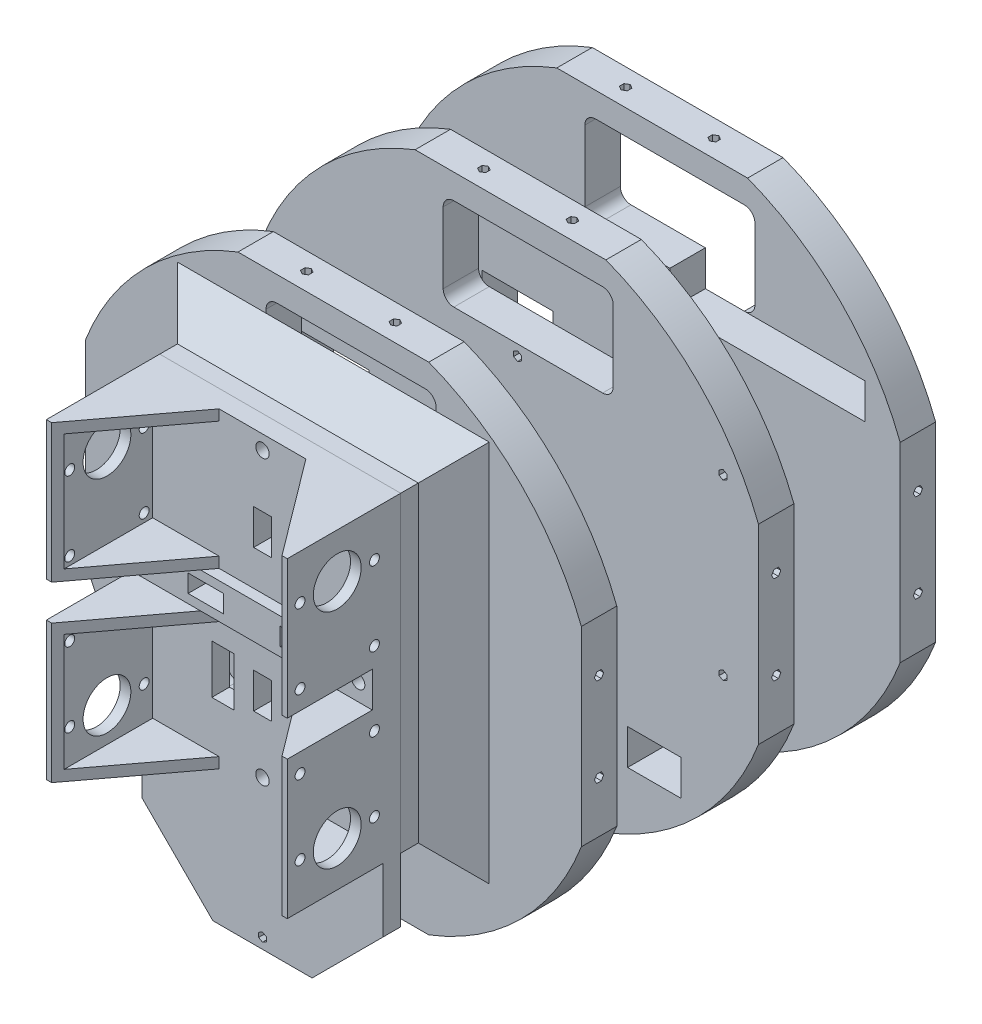
SolidWorks part; units mm, degrees
ref_plane "正面" through (0, 0, 0) normal (0, 0, 1) x (1, 0, 0)
ref_plane "平面" through (0, 0, 0) normal (0, 1, 0) x (1, 0, 0)
ref_plane "右側面" through (0, 0, 0) normal (1, 0, 0) x (0, 0, -1)
sketch "ｽｹｯﾁ5" plane through (0, 0, 0) normal (0, 1, 0) x (1, 0, 0)
  line L0 (-34, -32) -> (-34, 0)
  line L1 (-34, 0) -> (-10, 0)
  line L2 (-10, 0) -> (-34, -32)
  line L3 (-88, 0) -> (88, 0) construction
  dimension "D1" = 24
  dimension "D2" = 32
  dimension "D3" = 10
extrude "ﾎﾞｽ - 押し出し3" add sketch "ｽｹｯﾁ5" against normal blind 39 from offset 5 offset against normal yes
shell "ｼｪﾙ2" thickness 3
sketch "ｽｹｯﾁ7" plane through (-31, 0, 0) normal (1, 0, 0) x (0, 0, -1)
  line L0 (-3, -41) -> (-3, -8) construction
  line L1 (-26.4, -31.4) -> (-5.4, -31.4) construction
  line L2 (-26.4, -31.4) -> (-26.4, -10.4) construction
  line L3 (-26.4, -10.4) -> (-5.4, -10.4) construction
  line L4 (-5.4, -31.4) -> (-5.4, -10.4) construction
  line L5 (-3, -8) -> (-28, -8) construction
  circle A0 centre (-15.9, -31.4) radius 6.75
  circle A1 centre (-26.4, -31.4) radius 1.4
  circle A2 centre (-5.4, -31.4) radius 1.4
  circle A3 centre (-5.4, -10.4) radius 1.4
  circle A4 centre (-26.4, -10.4) radius 1.4
  point P10 (-15.9, -31.4)
  dimension "D3" = 2.8
  dimension "D6" = 13.5
  dimension "D1" = 21
  dimension "D2" = 21
  dimension "D4" = 2.4
  dimension "D5" = 2.4
extrude "ｶｯﾄ - 押し出し5" cut sketch "ｽｹｯﾁ7" against normal through all
sketch "ｽｹｯﾁ1" plane through (0, 0, 0) normal (0, 0, 1) x (1, 0, 0)
  line L0 (-34, -44) -> (-34, -5) construction
  line L1 (34, -44) -> (-34, -44)
  line L2 (34, -44) -> (34, 44)
  line L3 (34, 44) -> (-34, 44)
  line L4 (-34, -44) -> (-34, 44)
  line L5 (34, -44) -> (-34, 44) construction
  line L6 (34, 44) -> (-34, -44) construction
  line L7 (-34, -44) -> (-10, -44) construction
  point P0 (0, 0)
extrude "ﾎﾞｽ - 押し出し1" add sketch "ｽｹｯﾁ1" along normal blind 3 and the other way blind 2 contours L4 L1 L2 L3
sketch "ｽｹｯﾁ8" plane through (0, 0, 0) normal (0, 0, 1) x (1, 0, 0)
  line L0 (-34, -44) -> (-34, -5) construction
  line L1 (-34, -5) -> (-22.8121, -5)
  line L2 (-34, -5) -> (-34, -44)
  line L3 (-34, -44) -> (-22.8121, -44)
  line L4 (-22.8121, -5) -> (-22.8121, -44)
extrude "ｶｯﾄ - 押し出し6" cut sketch "ｽｹｯﾁ8" against normal blind 2 from vertex at 32 starting at point (-34, -5, 32)
mirror "ﾐﾗｰ1" about plane through (0, 0, 0) normal (1, 0, 0) of bodies 136 101
mirror "ﾐﾗｰ2" about plane through (0, 0, 0) normal (0, 1, 0) of bodies 134
sketch "ｽｹｯﾁ9" plane through (0, 0, 3) normal (0, 0, 1) x (1, 0, 0)
  circle A0 centre (-30, 0) radius 1.9
  circle A1 centre (0, 40) radius 1.9
  circle A2 centre (30, 0) radius 1.9
  circle A3 centre (0, -40) radius 1.9
  dimension "D1" = 3.8
  dimension "D2" = 30
  dimension "D3" = 30
  dimension "D4" = 40
  dimension "D5" = 40
extrude "ｶｯﾄ - 押し出し7" cut sketch "ｽｹｯﾁ9" against normal blind 10
sketch "ｽｹｯﾁ10" plane through (0, 0, 3) normal (0, 0, 1) x (1, 0, 0)
  line L1 (2.5, -25) -> (-2.5, -25)
  line L2 (2.5, -25) -> (2.5, -15)
  line L3 (2.5, -15) -> (-2.5, -15)
  line L4 (-2.5, -25) -> (-2.5, -15)
  line L5 (2.5, -25) -> (-2.5, -15) construction
  line L6 (2.5, -15) -> (-2.5, -25) construction
  line L7 (2.5, 15) -> (-2.5, 15)
  line L8 (2.5, 15) -> (2.5, 25)
  line L9 (2.5, 25) -> (-2.5, 25)
  line L10 (-2.5, 15) -> (-2.5, 25)
  line L11 (2.5, 15) -> (-2.5, 25) construction
  line L12 (2.5, 25) -> (-2.5, 15) construction
  point P0 (0, -20)
  point P5 (0, 20)
  dimension "D1" = 5
  dimension "D2" = 10
  dimension "D3" = 20
  dimension "D4" = 20
extrude "ｶｯﾄ - 押し出し8" cut sketch "ｽｹｯﾁ10" against normal blind 10
sketch "ｽｹｯﾁ11" plane through (0, 0, 3) normal (0, 0, 1) x (1, 0, 0)
  line L0 (31, 38.15) -> (31, 24.65) construction
  line L1 (14.3, 13.75) -> (8, 13.75)
  line L2 (14.3, 13.75) -> (14.3, 27.55)
  line L3 (14.3, 27.55) -> (8, 27.55)
  line L4 (8, 13.75) -> (8, 27.55)
  line L5 (14.3, 13.75) -> (8, 27.55) construction
  line L6 (14.3, 27.55) -> (8, 13.75) construction
  line L7 (-8, -27.55) -> (-14.3, -27.55)
  line L8 (-8, -27.55) -> (-8, -13.75)
  line L9 (-8, -13.75) -> (-14.3, -13.75)
  line L10 (-14.3, -27.55) -> (-14.3, -13.75)
  line L11 (-8, -27.55) -> (-14.3, -13.75) construction
  line L12 (-8, -13.75) -> (-14.3, -27.55) construction
  line L13 (31, 38.15) -> (31, 24.65)
  line L15 (-31, -38.15) -> (-31, -24.65) construction
  line L16 (-31, -38.15) -> (-31, -24.65)
  point P0 (11.15, 20.65)
  point P5 (-11.15, -20.65)
  point P15 (31, 31.4)
  point P20 (-31, -31.4)
  dimension "D1" = 6.3
  dimension "D2" = 3.85
  dimension "D3" = 17.65
  dimension "D4" = 23
  dimension "D5" = 3.85
  dimension "D6" = 23
extrude "ｶｯﾄ - 押し出し9" cut sketch "ｽｹｯﾁ11" against normal blind 10 contours L10 L7 L8 L9 | L4 L1 L2 L3
sketch "ｽｹｯﾁ12" plane through (0, 0, 3) normal (0, 0, 1) x (1, 0, 0)
  line L1 (-8, -2.5) -> (-18, -2.5)
  line L2 (-8, -2.5) -> (-8, 2.5)
  line L3 (-8, 2.5) -> (-18, 2.5)
  line L4 (-18, -2.5) -> (-18, 2.5)
  line L5 (-8, -2.5) -> (-18, 2.5) construction
  line L6 (-8, 2.5) -> (-18, -2.5) construction
  line L7 (18, -2.5) -> (8, -2.5)
  line L8 (18, -2.5) -> (18, 2.5)
  line L9 (18, 2.5) -> (8, 2.5)
  line L10 (8, -2.5) -> (8, 2.5)
  line L11 (18, -2.5) -> (8, 2.5) construction
  line L12 (18, 2.5) -> (8, -2.5) construction
  point P0 (-13, 0)
  point P5 (13, 0)
  dimension "D1" = 5
  dimension "D2" = 10
  dimension "D3" = 13
  dimension "D4" = 13
extrude "ｶｯﾄ - 押し出し10" cut sketch "ｽｹｯﾁ12" against normal blind 10
sketch "ｽｹｯﾁ13" plane through (0, -44, 0) normal (0, -1, 0) x (1, 0, 0)
  line L0 (34, -2) -> (34, 30) construction
  line L1 (-34, -2) -> (34, -2)
  line L2 (-34, -2) -> (-34, 3)
  line L3 (-34, 3) -> (34, 3)
  line L4 (34, -2) -> (34, 3)
  line L5 (12.25, 3) -> (-12.25, 3) construction
extrude "ﾎﾞｽ - 押し出し4" add sketch "ｽｹｯﾁ13" along normal blind 38
chamfer "面取り2" distance 20 angle 45 2 edges at (-34, -82, 0.5) (34, -82, 0.5)
sketch "ｽｹｯﾁ14" plane through (0, 0, -2) normal (0, 0, -1) x (-1, 0, 0)
  line L0 (14, -82) -> (-14, -82) construction
  line L1 (23.4, -79) -> (-23.4, -79) construction
  line L2 (23.4, -79) -> (23.4, -47.08) construction
  line L3 (23.4, -47.08) -> (-23.4, -47.08) construction
  line L4 (-23.4, -79) -> (-23.4, -47.08) construction
  line L5 (23.4, -79) -> (-23.4, -47.08) construction
  line L6 (23.4, -47.08) -> (-23.4, -79) construction
  line L8 (-23.4, -45.83) -> (-24.4825, -46.455)
  line L9 (-24.4825, -46.455) -> (-24.4825, -47.705)
  line L10 (-24.4825, -47.705) -> (-23.4, -48.33)
  line L11 (-23.4, -48.33) -> (-22.3175, -47.705)
  line L12 (-22.3175, -47.705) -> (-22.3175, -46.455)
  line L13 (-22.3175, -46.455) -> (-23.4, -45.83)
  line L14 (23.4, -45.83) -> (22.3175, -46.455)
  line L15 (22.3175, -46.455) -> (22.3175, -47.705)
  line L16 (22.3175, -47.705) -> (23.4, -48.33)
  line L17 (23.4, -48.33) -> (24.4825, -47.705)
  line L18 (24.4825, -47.705) -> (24.4825, -46.455)
  line L19 (24.4825, -46.455) -> (23.4, -45.83)
  line L20 (0, -77.75) -> (-1.0825, -78.375)
  line L21 (-1.0825, -78.375) -> (-1.0825, -79.625)
  line L22 (-1.0825, -79.625) -> (0, -80.25)
  line L23 (0, -80.25) -> (1.0825, -79.625)
  line L24 (1.0825, -79.625) -> (1.0825, -78.375)
  line L25 (1.0825, -78.375) -> (0, -77.75)
  circle A0 centre (-23.4, -47.08) radius 1.5
  circle A1 centre (23.4, -47.08) radius 1.5
  circle A2 centre (0, -79) radius 1.5
  circle A3 centre (-23.4, -47.08) radius 1.0825 construction
  circle A4 centre (23.4, -47.08) radius 1.0825 construction
  circle A5 centre (0, -79) radius 1.0825 construction
  point P0 (0, -63.04)
  point P12 (0, -82)
  dimension "D3" = 3
  dimension "D1" = 46.8
  dimension "D2" = 31.92
  dimension "D4" = 3
  dimension "D5" = 2.5
extrude "ｶｯﾄ - 押し出し11" cut sketch "ｽｹｯﾁ14" against normal blind 35 contours L24 L25 L20 L21 L22 L23 | L12 L13 L8 L9 L10 L11 | L18 L19 L14 L15 L16 L17
sketch "ｽｹｯﾁ15" plane through (0, 0, 3) normal (0, 0, 1) x (1, 0, 0)
  line L0 (-18, 2.5) -> (-18, -2.5) construction
  line L1 (34, -5) -> (-34, -5)
  line L2 (34, -5) -> (34, 5)
  line L3 (34, 5) -> (-34, 5)
  line L4 (-34, -5) -> (-34, 5)
  line L5 (-18, -2.5) -> (-8, -2.5) construction
  line L6 (-8, 2.5) -> (-18, 2.5) construction
  line L7 (-8, -2.5) -> (-8, 2.5) construction
  line L8 (8, 2.5) -> (8, -2.5) construction
  line L9 (18, 2.5) -> (8, 2.5) construction
  line L10 (8, -2.5) -> (18, -2.5) construction
  line L11 (18, -2.5) -> (18, 2.5) construction
  line L12 (-18, 2.5) -> (-18, -2.5)
  line L13 (-18, -2.5) -> (-8, -2.5)
  line L14 (-8, 2.5) -> (-18, 2.5)
  line L15 (-8, -2.5) -> (-8, 2.5)
  line L16 (8, 2.5) -> (8, -2.5)
  line L17 (18, 2.5) -> (8, 2.5)
  line L18 (8, -2.5) -> (18, -2.5)
  line L19 (18, -2.5) -> (18, 2.5)
  circle A0 centre (30, 0) radius 1.9 construction
  circle A1 centre (-30, 0) radius 1.9 construction
  circle A2 centre (30, 0) radius 1.9
  circle A3 centre (-30, 0) radius 1.9
extrude "ﾎﾞｽ - 押し出し5" add sketch "ｽｹｯﾁ15" along normal blind 3
sketch "ｽｹｯﾁ16" plane through (0, 0, -2) normal (0, 0, -1) x (-1, 0, 0)
  line L0 (-19, -29) -> (-19, 29) construction
  line L5 (34, -44) -> (-34, -44)
  line L6 (34, -44) -> (34, 44)
  line L7 (34, 44) -> (-34, 44)
  line L8 (-34, -44) -> (-34, 44)
  line L9 (34, -44) -> (-34, 44) construction
  line L10 (34, 44) -> (-34, -44) construction
  line L11 (19, 29) -> (-19, 29) construction
  line L12 (19, -29) -> (19, 29) construction
  line L13 (19, -29) -> (-19, -29) construction
  line L14 (-25, -35) -> (-25, 35)
  line L15 (25, 35) -> (-25, 35)
  line L16 (25, -35) -> (25, 35)
  line L17 (25, -35) -> (-25, -35)
  circle A1 centre (0, -5) radius 80 construction
  point P4 (0, 0)
  dimension "D1" = 160
  dimension "D2" = 5
  dimension "D3" = 15
  dimension "D4" = 6
extrude "ﾎﾞｽ - 押し出し7" add sketch "ｽｹｯﾁ16" along normal blind 10 separate body
sketch "ｽｹｯﾁ48" plane through (0, 0, -12) normal (0, 0, -1) x (-1, 0, 0)
  line L4 (-34, 44) -> (-34, -44)
  line L5 (-34, -44) -> (34, -44)
  line L6 (34, -44) -> (34, 44)
  line L7 (34, 44) -> (-34, 44)
  line L8 (-34, 44) -> (-34, -44)
  line L9 (-34, -44) -> (34, -44)
  line L10 (34, -44) -> (34, 44)
  line L11 (34, 44) -> (-34, 44)
  dimension "D1" = 0
extrude "ﾎﾞｽ - 押し出し14" add sketch "ｽｹｯﾁ48" along normal blind 5
sketch "ｽｹｯﾁ18" plane through (0, 0, -17) normal (0, 0, -1) x (-1, 0, 0)
  circle A0 centre (0, -5) radius 75
  circle A1 centre (0, -5) radius 80 construction
  dimension "D1" = 150
extrude "ﾎﾞｽ - 押し出し8" add sketch "ｽｹｯﾁ18" along normal blind 10
ref_plane "平面1" through (0, 0, -107) normal (0, 0, -1) x (-1, 0, 0)
sketch "ｽｹｯﾁ20" plane through (0, 0, -107) normal (0, 0, -1) x (-1, 0, 0)
  circle A1 centre (0, -5) radius 75
  circle A2 centre (0, -5) radius 75 construction
extrude "ﾎﾞｽ - 押し出し10" add sketch "ｽｹｯﾁ20" along normal blind 10
ref_plane "平面2" through (0, 0, -67) normal (0, 0, -1) x (-1, 0, 0)
sketch "ｽｹｯﾁ50" plane through (0, 0, -67) normal (0, 0, -1) x (-1, 0, 0)
  circle A1 centre (0, -5) radius 75
  circle A2 centre (0, -5) radius 75
  dimension "D1" = 0
extrude "ﾎﾞｽ - 押し出し15" add sketch "ｽｹｯﾁ50" along normal blind 10 separate body
sketch "ｽｹｯﾁ22" plane through (0, 0, -77) normal (0, 0, -1) x (-1, 0, 0)
  line L1 (-2, -20) -> (-60, -20) construction
  line L2 (-2, -20) -> (-2, 29) construction
  line L3 (-2, 29) -> (-60, 29) construction
  line L4 (-60, -20) -> (-60, 29) construction
  line L5 (-2, -20) -> (-60, 29) construction
  line L6 (-2, 29) -> (-60, -20) construction
  line L7 (-60, 30.3) -> (-61.1258, 29.65)
  line L8 (-61.1258, 29.65) -> (-61.1258, 28.35)
  line L9 (-61.1258, 28.35) -> (-60, 27.7)
  line L10 (-60, 27.7) -> (-58.8742, 28.35)
  line L11 (-58.8742, 28.35) -> (-58.8742, 29.65)
  line L12 (-58.8742, 29.65) -> (-60, 30.3)
  line L13 (-60, -18.7) -> (-61.1258, -19.35)
  line L14 (-61.1258, -19.35) -> (-61.1258, -20.65)
  line L15 (-61.1258, -20.65) -> (-60, -21.3)
  line L16 (-60, -21.3) -> (-58.8742, -20.65)
  line L17 (-58.8742, -20.65) -> (-58.8742, -19.35)
  line L18 (-58.8742, -19.35) -> (-60, -18.7)
  line L19 (-2, -18.7) -> (-3.1258, -19.35)
  line L20 (-3.1258, -19.35) -> (-3.1258, -20.65)
  line L21 (-3.1258, -20.65) -> (-2, -21.3)
  line L22 (-2, -21.3) -> (-0.8742, -20.65)
  line L23 (-0.8742, -20.65) -> (-0.8742, -19.35)
  line L24 (-0.8742, -19.35) -> (-2, -18.7)
  line L25 (-2, 30.3) -> (-3.1258, 29.65)
  line L26 (-3.1258, 29.65) -> (-3.1258, 28.35)
  line L27 (-3.1258, 28.35) -> (-2, 27.7)
  line L28 (-2, 27.7) -> (-0.8742, 28.35)
  line L29 (-0.8742, 28.35) -> (-0.8742, 29.65)
  line L30 (-0.8742, 29.65) -> (-2, 30.3)
  circle A0 centre (-60, 29) radius 1.1258 construction
  circle A1 centre (-60, -20) radius 1.1258 construction
  circle A2 centre (-2, -20) radius 1.1258 construction
  circle A3 centre (-2, 29) radius 1.1258 construction
  point P0 (-31, 4.5)
  dimension "D1" = 58
  dimension "D2" = 49
  dimension "D3" = 2.6
  dimension "D4" = 20
  dimension "D5" = 60
extrude "ｶｯﾄ - 押し出し29" cut sketch "ｽｹｯﾁ22" against normal blind 10
sketch "ｽｹｯﾁ23" plane through (0, 0, -27) normal (0, 0, -1) x (-1, 0, 0)
  line L0 (-31, 38.15) -> (-31, 24.65) construction
  line L1 (31, -38.15) -> (31, -24.65) construction
  line L2 (-31, 38.15) -> (-31, 24.65)
  line L3 (31, -38.15) -> (31, -24.65)
  line L4 (8, -27.55) -> (14.3, -27.55)
  line L5 (14.3, -27.55) -> (14.3, -13.75)
  line L6 (14.3, -13.75) -> (8, -13.75)
  line L7 (8, -13.75) -> (8, -27.55)
  line L8 (8, -27.55) -> (14.3, -27.55)
  line L9 (14.3, -27.55) -> (14.3, -13.75)
  line L10 (14.3, -13.75) -> (8, -13.75)
  line L11 (8, -13.75) -> (8, -27.55)
  line L12 (-14.3, 13.75) -> (-8, 13.75)
  line L13 (-8, 13.75) -> (-8, 27.55)
  line L14 (-8, 27.55) -> (-14.3, 27.55)
  line L15 (-14.3, 27.55) -> (-14.3, 13.75)
  line L16 (-14.3, 13.75) -> (-8, 13.75)
  line L17 (-8, 13.75) -> (-8, 27.55)
  line L18 (-8, 27.55) -> (-14.3, 27.55)
  line L19 (-14.3, 27.55) -> (-14.3, 13.75)
  line L21 (-19.5914, -40.0452) -> (-29.5914, -40.0452)
  line L22 (-19.5914, -40.0452) -> (-19.5914, -35.0452)
  line L23 (-19.5914, -35.0452) -> (-29.5914, -35.0452)
  line L24 (-18, -2.5) -> (-8, -2.5)
  line L25 (-8, -2.5) -> (-8, 2.5)
  line L26 (-8, 2.5) -> (-18, 2.5)
  line L27 (-18, 2.5) -> (-18, -2.5)
  line L28 (-18, -2.5) -> (-8, -2.5)
  line L29 (-8, -2.5) -> (-8, 2.5)
  line L30 (-8, 2.5) -> (-18, 2.5)
  line L31 (-18, 2.5) -> (-18, -2.5)
  line L32 (8, -2.5) -> (18, -2.5)
  line L33 (18, -2.5) -> (18, 2.5)
  line L34 (18, 2.5) -> (8, 2.5)
  line L35 (8, 2.5) -> (8, -2.5)
  line L36 (8, -2.5) -> (18, -2.5)
  line L37 (18, -2.5) -> (18, 2.5)
  line L38 (18, 2.5) -> (8, 2.5)
  line L39 (8, 2.5) -> (8, -2.5)
  line L40 (-29.5914, -40.0452) -> (-29.5914, -35.0452)
  line L41 (14.4522, -40.3568) -> (4.4522, -40.3568)
  line L42 (14.4522, -40.3568) -> (14.4522, -35.3568)
  line L43 (14.4522, -35.3568) -> (4.4522, -35.3568)
  line L44 (4.4522, -40.3568) -> (4.4522, -35.3568)
  dimension "D5" = 10
  dimension "D6" = 5
  dimension "D7" = 5
  dimension "D8" = 10
  dimension "D1" = 0
  dimension "D2" = 0
  dimension "D3" = 0
  dimension "D4" = 0
extrude "ｶｯﾄ - 押し出し26" cut sketch "ｽｹｯﾁ23" against normal through all both and the other way through all contours L40 L21 L22 L23 | L44 L41 L42 L43
sketch "ｽｹｯﾁ24" plane through (0, 0, -77) normal (0, 0, -1) x (-1, 0, 0)
  line L19 (-4, -60.5) -> (-26, -60.5)
  line L20 (-4, -60.5) -> (-4, -55.5)
  line L21 (-4, -55.5) -> (-26, -55.5)
  line L22 (-26, -60.5) -> (-26, -55.5)
  line L23 (-4, -60.5) -> (-26, -55.5) construction
  line L24 (-4, -55.5) -> (-26, -60.5) construction
  line L25 (-22.5, -66.7) -> (-23.6258, -67.35)
  line L26 (-23.6258, -67.35) -> (-23.6258, -68.65)
  line L27 (-23.6258, -68.65) -> (-22.5, -69.3)
  line L28 (-22.5, -69.3) -> (-21.3742, -68.65)
  line L29 (-21.3742, -68.65) -> (-21.3742, -67.35)
  line L30 (-21.3742, -67.35) -> (-22.5, -66.7)
  line L31 (-7.5, -66.7) -> (-8.6258, -67.35)
  line L32 (-8.6258, -67.35) -> (-8.6258, -68.65)
  line L33 (-8.6258, -68.65) -> (-7.5, -69.3)
  line L34 (-7.5, -69.3) -> (-6.3742, -68.65)
  line L35 (-6.3742, -68.65) -> (-6.3742, -67.35)
  line L36 (-6.3742, -67.35) -> (-7.5, -66.7)
  circle A2 centre (-22.5, -68) radius 1.1258 construction
  circle A3 centre (-7.5, -68) radius 1.1258 construction
  point P9 (-15, -58)
  dimension "D7" = 5
  dimension "D8" = 22
  dimension "D9" = 2.6
  dimension "D10" = 15
  dimension "D11" = 7.5
  dimension "D12" = 10
  dimension "D2" = 15
  dimension "D3" = 58
extrude "ｶｯﾄ - 押し出し30" cut sketch "ｽｹｯﾁ24" against normal blind 10
sketch "ｽｹｯﾁ25" plane through (0, 0, -117) normal (0, 0, -1) x (-1, 0, 0)
  line L0 (9.9958, -75) -> (-70, -75)
  line L1 (70, -75) -> (9.9958, -75)
  line L2 (70, -75) -> (70, 65)
  line L3 (70, 65) -> (-70, 65)
  line L4 (-70, -75) -> (-70, 65)
  line L5 (70, -75) -> (-70, 65) construction
  line L6 (70, 65) -> (-70, -75) construction
  line L7 (94.2556, -94.1296) -> (-94.2556, -94.1296)
  line L8 (94.2556, -94.1296) -> (94.2556, 84.1296)
  line L9 (94.2556, 84.1296) -> (-94.2556, 84.1296)
  line L10 (-94.2556, -94.1296) -> (-94.2556, 84.1296)
  line L11 (94.2556, -94.1296) -> (-94.2556, 84.1296) construction
  line L12 (94.2556, 84.1296) -> (-94.2556, -94.1296) construction
  point P0 (0, -5)
  point P2 (0, -5)
  point P7 (0, -5)
  dimension "D1" = 140
extrude "ｶｯﾄ - 押し出し16" cut sketch "ｽｹｯﾁ25" against normal through all
chamfer "面取り3" distance 10 angle 45 4 edges at (0, -44, -17) (34, 0, -17) (0, 44, -17) (-34, 0, -17)
sketch "ｽｹｯﾁ28" plane through (0, 0, -117) normal (0, 0, -1) x (-1, 0, 0)
  line L0 (-26.9258, -75) -> (26.9258, -75) construction
  line L5 (-70, 21.9258) -> (-70, -31.9258)
  line L6 (-26.9258, -75) -> (26.9258, -75)
  line L7 (70, -31.9258) -> (70, 21.9258)
  line L8 (26.9258, 65) -> (-26.9258, 65)
  line L10 (-5, -75) -> (5, -75)
  arc A0 (-5, -75) -> (5, -75) centre (0, -75) ccw
  arc A5 (-26.9258, 65) -> (-70, 21.9258) centre (0, -5) ccw
  arc A6 (-70, -31.9258) -> (-26.9258, -75) centre (0, -5) ccw
  arc A7 (26.9258, -75) -> (70, -31.9258) centre (0, -5) ccw
  arc A8 (70, 21.9258) -> (26.9258, 65) centre (0, -5) ccw
  dimension "D1" = 5
  dimension "D2" = 0
extrude "ﾎﾞｽ - 押し出し11" add sketch "ｽｹｯﾁ28" against normal blind 10
sketch "ｽｹｯﾁ21" plane through (0, 0, -117) normal (0, 0, -1) x (-1, 0, 0)
  line L0 (23.4, -47.08) -> (-23.4, -47.08) construction
  line L1 (23.4, -75.96) -> (-23.4, -75.96) construction
  line L2 (23.4, -75.96) -> (23.4, -44.04) construction
  line L3 (23.4, -44.04) -> (-23.4, -44.04) construction
  line L4 (-23.4, -75.96) -> (-23.4, -44.04) construction
  line L5 (23.4, -75.96) -> (-23.4, -44.04) construction
  line L6 (23.4, -44.04) -> (-23.4, -75.96) construction
  line L7 (23.4, -79) -> (23.4, -47.08) construction
  line L8 (-23.4, -45.83) -> (-24.4825, -46.455) construction
  line L9 (-23.4, -42.79) -> (-24.4825, -43.415)
  line L10 (-24.4825, -43.415) -> (-24.4825, -44.665)
  line L11 (-24.4825, -44.665) -> (-23.4, -45.29)
  line L12 (-23.4, -45.29) -> (-22.3175, -44.665)
  line L13 (-22.3175, -44.665) -> (-22.3175, -43.415)
  line L14 (-22.3175, -43.415) -> (-23.4, -42.79)
  line L15 (23.4, -42.79) -> (22.3175, -43.415)
  line L16 (22.3175, -43.415) -> (22.3175, -44.665)
  line L17 (22.3175, -44.665) -> (23.4, -45.29)
  line L18 (23.4, -45.29) -> (24.4825, -44.665)
  line L19 (24.4825, -44.665) -> (24.4825, -43.415)
  line L20 (24.4825, -43.415) -> (23.4, -42.79)
  line L21 (0, -74.71) -> (-1.0825, -75.335)
  line L22 (-1.0825, -75.335) -> (-1.0825, -76.585)
  line L23 (-1.0825, -76.585) -> (0, -77.21)
  line L24 (0, -77.21) -> (1.0825, -76.585)
  line L25 (1.0825, -76.585) -> (1.0825, -75.335)
  line L26 (1.0825, -75.335) -> (0, -74.71)
  circle A0 centre (-23.4, -44.04) radius 1.0825 construction
  circle A1 centre (23.4, -44.04) radius 1.0825 construction
  circle A2 centre (0, -75.96) radius 1.0825 construction
  point P0 (0, -60)
  dimension "D1" = 60
extrude "ｶｯﾄ - 押し出し12" cut sketch "ｽｹｯﾁ21" against normal blind 10
sketch "ｽｹｯﾁ29" plane through (0, -75, 0) normal (0, -1, 0) x (1, 0, 0)
  line L0 (26.9258, -27) -> (-26.9258, -27) construction
  line L1 (12.5, -23.3) -> (13.6258, -22.65)
  line L2 (13.6258, -22.65) -> (13.6258, -21.35)
  line L3 (13.6258, -21.35) -> (12.5, -20.7)
  line L4 (12.5, -20.7) -> (11.3742, -21.35)
  line L5 (11.3742, -21.35) -> (11.3742, -22.65)
  line L6 (11.3742, -22.65) -> (12.5, -23.3)
  line L7 (-12.5, -23.3) -> (-11.3742, -22.65)
  line L8 (-11.3742, -22.65) -> (-11.3742, -21.35)
  line L9 (-11.3742, -21.35) -> (-12.5, -20.7)
  line L10 (-12.5, -20.7) -> (-13.6258, -21.35)
  line L11 (-13.6258, -21.35) -> (-13.6258, -22.65)
  line L12 (-13.6258, -22.65) -> (-12.5, -23.3)
  line L15 (26.9258, -17) -> (-26.9258, -17) construction
  line L16 (-82.5, -107) -> (82.5, -107) construction
  line L17 (12.5, -22) -> (-12.5, -22) construction
  line L18 (12.5, -22) -> (12.5, -112) construction
  line L19 (12.5, -112) -> (-12.5, -112) construction
  line L20 (-12.5, -22) -> (-12.5, -112) construction
  line L22 (12.5, -113.3) -> (13.6258, -112.65)
  line L23 (13.6258, -112.65) -> (13.6258, -111.35)
  line L24 (13.6258, -111.35) -> (12.5, -110.7)
  line L25 (12.5, -110.7) -> (11.3742, -111.35)
  line L26 (11.3742, -111.35) -> (11.3742, -112.65)
  line L27 (11.3742, -112.65) -> (12.5, -113.3)
  line L28 (-12.5, -113.3) -> (-11.3742, -112.65)
  line L29 (-11.3742, -112.65) -> (-11.3742, -111.35)
  line L30 (-11.3742, -111.35) -> (-12.5, -110.7)
  line L31 (-12.5, -110.7) -> (-13.6258, -111.35)
  line L32 (-13.6258, -111.35) -> (-13.6258, -112.65)
  line L33 (-13.6258, -112.65) -> (-12.5, -113.3)
  circle A0 centre (12.5, -22) radius 1.1258 construction
  circle A1 centre (-12.5, -22) radius 1.1258 construction
  circle A2 centre (12.5, -112) radius 1.1258 construction
  circle A3 centre (-12.5, -112) radius 1.1258 construction
  point P19 (0, -27)
  dimension "D1" = 2.6
  dimension "D2" = 25
  dimension "D3" = 12.5
  dimension "D4" = 5
  dimension "D5" = 5
extrude "ｶｯﾄ - 押し出し18" cut sketch "ｽｹｯﾁ29" against normal blind 10
sketch "ｽｹｯﾁ38" plane through (0, 0, 0) normal (1, 0, 0) x (0, 0, -1)
  line L0 (137.5786, -5) -> (-60.0304, -5)
pattern_circular "円形ﾊﾟﾀｰﾝ1" count 4 over 360 about axis through (0, -5, 0) along (0, 0, 1) of "ｶｯﾄ - 押し出し18"
sketch "ｽｹｯﾁ33" plane through (0, 0, -27) normal (0, 0, -1) x (-1, 0, 0)
  line L1 (19, 32) -> (-29, 32)
  line L2 (19, 32) -> (19, 58)
  line L3 (19, 58) -> (-29, 58)
  line L4 (-29, 32) -> (-29, 58)
  line L5 (19, 32) -> (-29, 58) construction
  line L6 (19, 58) -> (-29, 32) construction
  point P0 (-5, 45)
  dimension "D1" = 26
  dimension "D2" = 48
  dimension "D3" = 45
  dimension "D4" = 5
extrude "ｶｯﾄ - 押し出し20" cut sketch "ｽｹｯﾁ33" against normal blind 10 and the other way through all
fillet "ﾌｨﾚｯﾄ1" radius 3 8 edges at (-25, -35, -7) (25, -35, -7) (-25, 35, -7) (-19, 32, -22) (29, 32, -22) (-19, 58, -22) (25, 35, -7) (29, 58, -22)
sketch "ｽｹｯﾁ39" plane through (0, -75, 0) normal (0, -1, 0) x (1, 0, 0)
  line L0 (-11.3742, -72.65) -> (-11.3742, -71.35)
  line L1 (-11.3742, -71.35) -> (-12.5, -70.7)
  line L2 (-12.5, -70.7) -> (-13.6258, -71.35)
  line L3 (-13.6258, -71.35) -> (-13.6258, -72.65)
  line L4 (-13.6258, -72.65) -> (-12.5, -73.3)
  line L5 (-12.5, -73.3) -> (-11.3742, -72.65)
  line L6 (-12.5, -23.3) -> (-11.3742, -22.65)
  line L7 (-11.3742, -22.65) -> (-11.3742, -21.35)
  line L8 (-11.3742, -21.35) -> (-12.5, -20.7)
  line L9 (-12.5, -20.7) -> (-13.6258, -21.35)
  line L10 (-13.6258, -21.35) -> (-13.6258, -22.65)
  line L11 (-13.6258, -22.65) -> (-12.5, -23.3)
  line L12 (-12.5, -23.3) -> (-11.3742, -22.65)
  line L13 (-11.3742, -22.65) -> (-11.3742, -21.35)
  line L14 (-11.3742, -21.35) -> (-12.5, -20.7)
  line L15 (-12.5, -20.7) -> (-13.6258, -21.35)
  line L16 (-13.6258, -21.35) -> (-13.6258, -22.65)
  line L17 (-13.6258, -22.65) -> (-12.5, -23.3)
  line L18 (12.5, -23.3) -> (13.6258, -22.65)
  line L19 (13.6258, -22.65) -> (13.6258, -21.35)
  line L20 (13.6258, -21.35) -> (12.5, -20.7)
  line L21 (12.5, -20.7) -> (11.3742, -21.35)
  line L22 (11.3742, -21.35) -> (11.3742, -22.65)
  line L23 (11.3742, -22.65) -> (12.5, -23.3)
  line L24 (12.5, -23.3) -> (13.6258, -22.65)
  line L25 (13.6258, -22.65) -> (13.6258, -21.35)
  line L26 (13.6258, -21.35) -> (12.5, -20.7)
  line L27 (12.5, -20.7) -> (11.3742, -21.35)
  line L28 (11.3742, -21.35) -> (11.3742, -22.65)
  line L29 (11.3742, -22.65) -> (12.5, -23.3)
  line L30 (-11.3742, -112.65) -> (-11.3742, -111.35)
  line L31 (-11.3742, -111.35) -> (-12.5, -110.7)
  line L32 (-12.5, -110.7) -> (-13.6258, -111.35)
  line L33 (-13.6258, -111.35) -> (-13.6258, -112.65)
  line L34 (-13.6258, -112.65) -> (-12.5, -113.3)
  line L35 (-12.5, -113.3) -> (-11.3742, -112.65)
  line L36 (-11.3742, -112.65) -> (-11.3742, -111.35)
  line L37 (-11.3742, -111.35) -> (-12.5, -110.7)
  line L38 (-12.5, -110.7) -> (-13.6258, -111.35)
  line L39 (-13.6258, -111.35) -> (-13.6258, -112.65)
  line L40 (-13.6258, -112.65) -> (-12.5, -113.3)
  line L41 (-12.5, -113.3) -> (-11.3742, -112.65)
  line L42 (11.3742, -111.35) -> (11.3742, -112.65)
  line L43 (11.3742, -112.65) -> (12.5, -113.3)
  line L44 (12.5, -113.3) -> (13.6258, -112.65)
  line L45 (13.6258, -112.65) -> (13.6258, -111.35)
  line L46 (13.6258, -111.35) -> (12.5, -110.7)
  line L47 (12.5, -110.7) -> (11.3742, -111.35)
  line L48 (11.3742, -111.35) -> (11.3742, -112.65)
  line L49 (11.3742, -112.65) -> (12.5, -113.3)
  line L50 (12.5, -113.3) -> (13.6258, -112.65)
  line L51 (13.6258, -112.65) -> (13.6258, -111.35)
  line L52 (13.6258, -111.35) -> (12.5, -110.7)
  line L53 (12.5, -110.7) -> (11.3742, -111.35)
  line L54 (11.3742, -71.35) -> (11.3742, -72.65)
  line L55 (11.3742, -72.65) -> (12.5, -73.3)
  line L56 (12.5, -73.3) -> (13.6258, -72.65)
  line L57 (13.6258, -72.65) -> (13.6258, -71.35)
  line L58 (13.6258, -71.35) -> (12.5, -70.7)
  line L59 (12.5, -70.7) -> (11.3742, -71.35)
  dimension "D6" = 40
  dimension "D1" = 0
  dimension "D2" = 0
  dimension "D3" = 0
  dimension "D4" = 0
  dimension "D5" = 2
extrude "ｶｯﾄ - 押し出し24" cut sketch "ｽｹｯﾁ39" against normal blind 10
pattern_circular "円形ﾊﾟﾀｰﾝ2" count 4 over 360 about axis through (0, -5, 0) along (0, 0, 1) of "ｶｯﾄ - 押し出し24"
sketch "ｽｹｯﾁ40" plane through (0, 0, -117) normal (0, 0, -1) x (-1, 0, 0)
  line L1 (48, -10) -> (28, -10)
  line L2 (48, -10) -> (48, 5)
  line L3 (48, 5) -> (28, 5)
  line L4 (28, -10) -> (28, 5)
  dimension "D1" = 15
  dimension "D2" = 20
  dimension "D3" = 10
  dimension "D4" = 30
extrude "ｶｯﾄ - 押し出し25" cut sketch "ｽｹｯﾁ40" against normal through all
sketch "ｽｹｯﾁ51" plane through (0, -75, 0) normal (0, -1, 0) x (1, 0, 0)
  line L6 (12.5, -23.3) -> (13.6258, -22.65)
  line L7 (13.6258, -22.65) -> (13.6258, -21.35)
  line L8 (13.6258, -21.35) -> (12.5, -20.7)
  line L9 (12.5, -20.7) -> (11.3742, -21.35)
  line L10 (11.3742, -21.35) -> (11.3742, -22.65)
  line L11 (11.3742, -22.65) -> (12.5, -23.3)
  line L12 (12.5, -23.3) -> (13.6258, -22.65)
  line L13 (13.6258, -22.65) -> (13.6258, -21.35)
  line L14 (13.6258, -21.35) -> (12.5, -20.7)
  line L15 (12.5, -20.7) -> (11.3742, -21.35)
  line L16 (11.3742, -21.35) -> (11.3742, -22.65)
  line L17 (11.3742, -22.65) -> (12.5, -23.3)
  line L18 (-12.5, -23.3) -> (-11.3742, -22.65)
  line L19 (-11.3742, -22.65) -> (-11.3742, -21.35)
  line L20 (-11.3742, -21.35) -> (-12.5, -20.7)
  line L21 (-12.5, -20.7) -> (-13.6258, -21.35)
  line L22 (-13.6258, -21.35) -> (-13.6258, -22.65)
  line L23 (-13.6258, -22.65) -> (-12.5, -23.3)
  line L24 (-12.5, -23.3) -> (-11.3742, -22.65)
  line L25 (-11.3742, -22.65) -> (-11.3742, -21.35)
  line L26 (-11.3742, -21.35) -> (-12.5, -20.7)
  line L27 (-12.5, -20.7) -> (-13.6258, -21.35)
  line L28 (-13.6258, -21.35) -> (-13.6258, -22.65)
  line L29 (-13.6258, -22.65) -> (-12.5, -23.3)
  line L30 (11.3742, -112.65) -> (12.5, -113.3)
  line L31 (12.5, -113.3) -> (13.6258, -112.65)
  line L32 (13.6258, -112.65) -> (13.6258, -111.35)
  line L33 (13.6258, -111.35) -> (12.5, -110.7)
  line L34 (12.5, -110.7) -> (11.3742, -111.35)
  line L35 (11.3742, -111.35) -> (11.3742, -112.65)
  line L36 (11.3742, -112.65) -> (12.5, -113.3)
  line L37 (12.5, -113.3) -> (13.6258, -112.65)
  line L38 (13.6258, -112.65) -> (13.6258, -111.35)
  line L39 (13.6258, -111.35) -> (12.5, -110.7)
  line L40 (12.5, -110.7) -> (11.3742, -111.35)
  line L41 (11.3742, -111.35) -> (11.3742, -112.65)
  line L42 (-13.6258, -111.35) -> (-13.6258, -112.65)
  line L43 (-13.6258, -112.65) -> (-12.5, -113.3)
  line L44 (-12.5, -113.3) -> (-11.3742, -112.65)
  line L45 (-11.3742, -112.65) -> (-11.3742, -111.35)
  line L46 (-11.3742, -111.35) -> (-12.5, -110.7)
  line L47 (-12.5, -110.7) -> (-13.6258, -111.35)
  line L48 (-13.6258, -111.35) -> (-13.6258, -112.65)
  line L49 (-13.6258, -112.65) -> (-12.5, -113.3)
  line L50 (-12.5, -113.3) -> (-11.3742, -112.65)
  line L51 (-11.3742, -112.65) -> (-11.3742, -111.35)
  line L52 (-11.3742, -111.35) -> (-12.5, -110.7)
  line L53 (-12.5, -110.7) -> (-13.6258, -111.35)
  line L54 (12.5, -73.3) -> (13.6258, -72.65)
  line L55 (13.6258, -72.65) -> (13.6258, -71.35)
  line L56 (13.6258, -71.35) -> (12.5, -70.7)
  line L57 (12.5, -70.7) -> (11.3742, -71.35)
  line L58 (11.3742, -71.35) -> (11.3742, -72.65)
  line L59 (11.3742, -72.65) -> (12.5, -73.3)
  line L60 (12.5, -73.3) -> (13.6258, -72.65)
  line L61 (13.6258, -72.65) -> (13.6258, -71.35)
  line L62 (13.6258, -71.35) -> (12.5, -70.7)
  line L63 (12.5, -70.7) -> (11.3742, -71.35)
  line L64 (11.3742, -71.35) -> (11.3742, -72.65)
  line L65 (11.3742, -72.65) -> (12.5, -73.3)
  line L66 (-13.6258, -72.65) -> (-12.5, -73.3)
  line L67 (-13.6258, -71.35) -> (-13.6258, -72.65)
  line L68 (-12.5, -70.7) -> (-13.6258, -71.35)
  line L69 (-11.3742, -71.35) -> (-12.5, -70.7)
  line L70 (-11.3742, -72.65) -> (-11.3742, -71.35)
  line L71 (-12.5, -73.3) -> (-11.3742, -72.65)
  line L72 (-13.6258, -72.65) -> (-12.5, -73.3)
  line L73 (-13.6258, -71.35) -> (-13.6258, -72.65)
  line L74 (-12.5, -70.7) -> (-13.6258, -71.35)
  line L75 (-11.3742, -71.35) -> (-12.5, -70.7)
  line L76 (-11.3742, -72.65) -> (-11.3742, -71.35)
  line L77 (-12.5, -73.3) -> (-11.3742, -72.65)
  dimension "D1" = 0
  dimension "D2" = 0
  dimension "D3" = 0
  dimension "D4" = 0
  dimension "D5" = 0
  dimension "D6" = 0
extrude "ｶｯﾄ - 押し出し31" cut sketch "ｽｹｯﾁ51" against normal blind 10
pattern_circular "円形ﾊﾟﾀｰﾝ3" count 4 over 360 about axis through (0, -5, 0) along (0, 0, 1) of "ｶｯﾄ - 押し出し31"
sketch "ｽｹｯﾁ43" plane through (0, 0, -2) normal (0, 0, 1) x (1, 0, 0)
  line L1 (0, 41.3) -> (-1.1258, 40.65)
  line L2 (-1.1258, 40.65) -> (-1.1258, 39.35)
  line L3 (-1.1258, 39.35) -> (0, 38.7)
  line L4 (0, 38.7) -> (1.1258, 39.35)
  line L5 (1.1258, 39.35) -> (1.1258, 40.65)
  line L6 (1.1258, 40.65) -> (0, 41.3)
  line L7 (0, -38.7) -> (-1.1258, -39.35)
  line L8 (-1.1258, -39.35) -> (-1.1258, -40.65)
  line L9 (-1.1258, -40.65) -> (0, -41.3)
  line L10 (0, -41.3) -> (1.1258, -40.65)
  line L11 (1.1258, -40.65) -> (1.1258, -39.35)
  line L12 (1.1258, -39.35) -> (0, -38.7)
  line L13 (-30, 1.3) -> (-31.1258, 0.65)
  line L14 (-31.1258, 0.65) -> (-31.1258, -0.65)
  line L15 (-31.1258, -0.65) -> (-30, -1.3)
  line L16 (-30, -1.3) -> (-28.8742, -0.65)
  line L17 (-28.8742, -0.65) -> (-28.8742, 0.65)
  line L18 (-28.8742, 0.65) -> (-30, 1.3)
  line L19 (30, 1.3) -> (28.8742, 0.65)
  line L20 (28.8742, 0.65) -> (28.8742, -0.65)
  line L21 (28.8742, -0.65) -> (30, -1.3)
  line L22 (30, -1.3) -> (31.1258, -0.65)
  line L23 (31.1258, -0.65) -> (31.1258, 0.65)
  line L24 (31.1258, 0.65) -> (30, 1.3)
  circle A0 centre (0, 40) radius 1.1258 construction
  circle A1 centre (0, -40) radius 1.9
  circle A2 centre (0, -40) radius 1.9 construction
  circle A3 centre (30, 0) radius 1.9
  circle A4 centre (30, 0) radius 1.9 construction
  circle A5 centre (0, 40) radius 1.9
  circle A6 centre (0, 40) radius 1.9 construction
  circle A7 centre (-30, 0) radius 1.9
  circle A8 centre (-30, 0) radius 1.9 construction
  circle A9 centre (0, -40) radius 1.1258 construction
  circle A10 centre (-30, 0) radius 1.1258 construction
  circle A11 centre (30, 0) radius 1.1258 construction
  dimension "D5" = 2.6
  dimension "D1" = 0
  dimension "D2" = 0
  dimension "D3" = 0
  dimension "D4" = 0
extrude "ｶｯﾄ - 押し出し27" cut sketch "ｽｹｯﾁ43" against normal blind 10
fillet "ﾌｨﾚｯﾄ2" radius 3 4 edges at (29, 58, -72) (29, 32, -72) (-19, 58, -72) (-19, 32, -72)
fillet "ﾌｨﾚｯﾄ3" radius 3 4 edges at (29, 32, -112) (29, 58, -112) (-19, 58, -112) (-19, 32, -112)
sketch "ｽｹｯﾁ52" plane through (0, 0, -77) normal (0, 0, -1) x (-1, 0, 0)
  line L1 (-33.0614, -56.0083) -> (-48.0614, -56.0083)
  line L2 (-33.0614, -56.0083) -> (-33.0614, -46.0083)
  line L3 (-33.0614, -46.0083) -> (-48.0614, -46.0083)
  line L4 (-48.0614, -56.0083) -> (-48.0614, -46.0083)
  line L5 (-33.0614, -56.0083) -> (-48.0614, -46.0083) construction
  line L6 (-33.0614, -46.0083) -> (-48.0614, -56.0083) construction
  point P0 (-40.5614, -51.0083)
  dimension "D1" = 15
  dimension "D2" = 10
extrude "ｶｯﾄ - 押し出し32" cut sketch "ｽｹｯﾁ52" against normal blind 10
sketch "ｽｹｯﾁ53" plane through (0, 0, -117) normal (0, 0, -1) x (-1, 0, 0)
  line L0 (-26, 32) -> (16, 32) construction
  line L1 (-5, 32) -> (-60, 32)
  line L2 (-5, 32) -> (-5, 22)
  line L3 (-5, 22) -> (-60, 22)
  line L4 (-60, 32) -> (-60, 22)
  line L5 (-5, 32) -> (-60, 22) construction
  line L6 (-5, 22) -> (-60, 32) construction
  point P0 (-32.5, 27)
  dimension "D1" = 55
  dimension "D2" = 10
  dimension "D3" = 0
extrude "ｶｯﾄ - 押し出し33" cut sketch "ｽｹｯﾁ53" against normal blind 10
sketch "ｽｹｯﾁ54" plane through (0, 0, -77) normal (0, 0, -1) x (-1, 0, 0)
  line L0 (70, -31.9258) -> (70, 21.9258) construction
  line L1 (60, 4.6336) -> (40, 4.6336)
  line L2 (60, 4.6336) -> (60, -10.3664)
  line L3 (60, -10.3664) -> (40, -10.3664)
  line L4 (40, 4.6336) -> (40, -10.3664)
  line L5 (60, 4.6336) -> (40, -10.3664) construction
  line L6 (60, -10.3664) -> (40, 4.6336) construction
  point P0 (50, -2.8664)
  dimension "D1" = 10
  dimension "D2" = 15
  dimension "D3" = 20
extrude "ｶｯﾄ - 押し出し34" cut sketch "ｽｹｯﾁ54" against normal blind 10
sketch "ｽｹｯﾁ55" plane through (0, 0, -12) normal (0, 0, 1) x (1, 0, 0)
  line L0 (-31, -38.15) -> (-31, -24.65) construction
  line L1 (31, 38.15) -> (31, 24.65) construction
  line L2 (-31, -38.15) -> (-31, -24.65)
  line L3 (31, 38.15) -> (31, 24.65)
  line L4 (8, 13.75) -> (14.3, 13.75)
  line L5 (8, 27.55) -> (8, 13.75)
  line L6 (14.3, 27.55) -> (8, 27.55)
  line L7 (14.3, 13.75) -> (14.3, 27.55)
  line L8 (8, 13.75) -> (14.3, 13.75)
  line L9 (8, 27.55) -> (8, 13.75)
  line L10 (14.3, 27.55) -> (8, 27.55)
  line L11 (14.3, 13.75) -> (14.3, 27.55)
  line L12 (-14.3, -27.55) -> (-8, -27.55)
  line L13 (-14.3, -13.75) -> (-14.3, -27.55)
  line L14 (-8, -13.75) -> (-14.3, -13.75)
  line L15 (-8, -27.55) -> (-8, -13.75)
  line L16 (-14.3, -27.55) -> (-8, -27.55)
  line L17 (-14.3, -13.75) -> (-14.3, -27.55)
  line L18 (-8, -13.75) -> (-14.3, -13.75)
  line L19 (-8, -27.55) -> (-8, -13.75)
  line L20 (-14.4522, -40.3568) -> (-4.4522, -40.3568)
  line L21 (-4.4522, -40.3568) -> (-4.4522, -35.3568)
  line L22 (-4.4522, -35.3568) -> (-14.4522, -35.3568)
  line L23 (-14.4522, -35.3568) -> (-14.4522, -40.3568)
  line L24 (-14.4522, -40.3568) -> (-4.4522, -40.3568)
  line L25 (-4.4522, -40.3568) -> (-4.4522, -35.3568)
  line L26 (-4.4522, -35.3568) -> (-14.4522, -35.3568)
  line L27 (-14.4522, -35.3568) -> (-14.4522, -40.3568)
  line L28 (-18, 2.5) -> (-18, -2.5)
  line L29 (-8, 2.5) -> (-18, 2.5)
  line L30 (-8, -2.5) -> (-8, 2.5)
  line L31 (-18, -2.5) -> (-8, -2.5)
  line L32 (-18, 2.5) -> (-18, -2.5)
  line L33 (-8, 2.5) -> (-18, 2.5)
  line L34 (-8, -2.5) -> (-8, 2.5)
  line L35 (-18, -2.5) -> (-8, -2.5)
  line L36 (18, 2.5) -> (8, 2.5)
  line L37 (8, 2.5) -> (8, -2.5)
  line L38 (8, -2.5) -> (18, -2.5)
  line L39 (18, -2.5) -> (18, 2.5)
  line L40 (18, 2.5) -> (8, 2.5)
  line L41 (8, 2.5) -> (8, -2.5)
  line L42 (8, -2.5) -> (18, -2.5)
  line L43 (18, -2.5) -> (18, 2.5)
  line L44 (19.5914, -40.0452) -> (29.5914, -40.0452)
  line L45 (29.5914, -40.0452) -> (29.5914, -35.0452)
  line L46 (29.5914, -35.0452) -> (19.5914, -35.0452)
  line L47 (19.5914, -35.0452) -> (19.5914, -40.0452)
  line L48 (19.5914, -40.0452) -> (29.5914, -40.0452)
  line L49 (29.5914, -40.0452) -> (29.5914, -35.0452)
  line L50 (29.5914, -35.0452) -> (19.5914, -35.0452)
  line L51 (19.5914, -35.0452) -> (19.5914, -40.0452)
  dimension "D1" = 0
  dimension "D2" = 0
  dimension "D3" = 0
  dimension "D4" = 0
  dimension "D5" = 0
  dimension "D6" = 0
extrude "ｶｯﾄ - 押し出し35" cut sketch "ｽｹｯﾁ55" against normal through all contours L16 L19 L18 L17 | L42 L43 L40 L41 | L32 L35 L34 L33 | L8 L11 L10 L9
equation "\"D3@ｽｹｯﾁ9\"=\"D2@ｽｹｯﾁ9\""
equation "\"D5@ｽｹｯﾁ9\"=\"D4@ｽｹｯﾁ9\""
equation "\"D4@ｽｹｯﾁ10\"=\"D3@ｽｹｯﾁ10\""
equation "\"D4@ｽｹｯﾁ11\"=26-3"
equation "\"D6@ｽｹｯﾁ11\"=26-3"
equation "\"D4@ｽｹｯﾁ12\"=\"D3@ｽｹｯﾁ12\""
equation "\"D3@ｽｹｯﾁ29\"=\"D2@ｽｹｯﾁ29\"/2"
equation "\"D11@ｽｹｯﾁ24\"=\"D10@ｽｹｯﾁ24\"/2"
